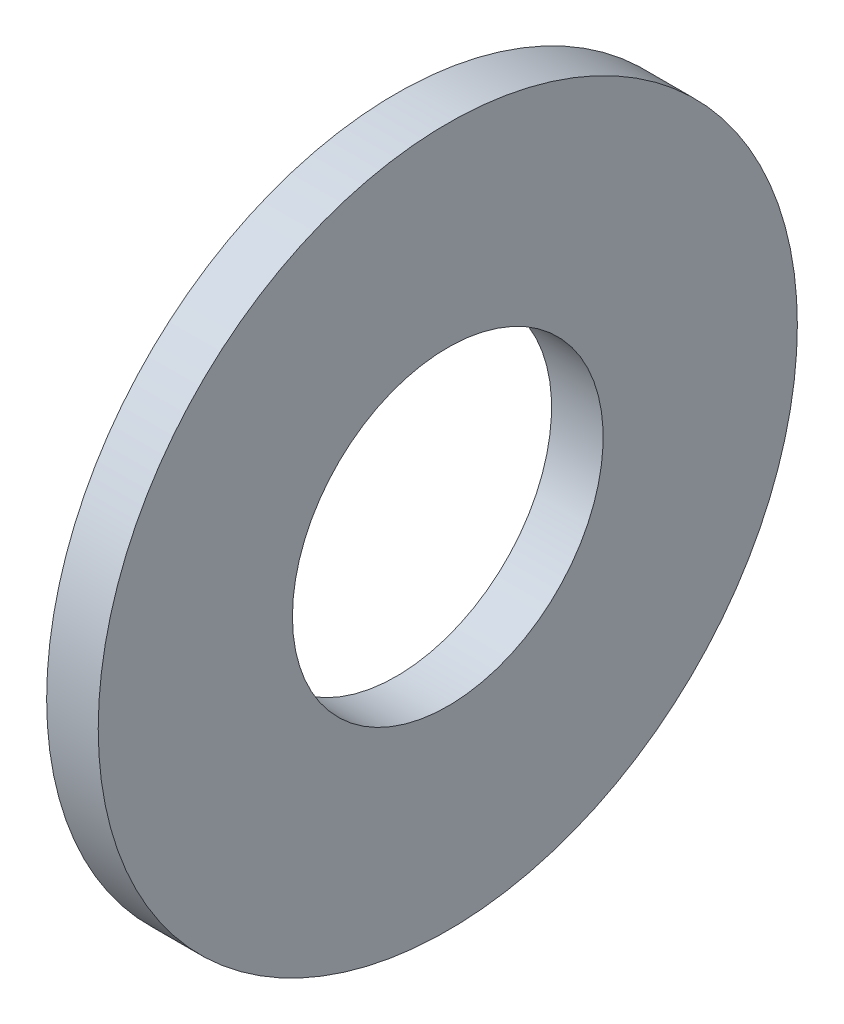
SolidWorks part; units mm, degrees
material "Plain Carbon Steel"
ref_plane "Plane1" through (0, 0, 0) normal (0, 0, 1) x (1, 0, 0)
ref_plane "Plane2" through (0, 0, 0) normal (0, 1, 0) x (1, 0, 0)
ref_plane "Plane3" through (0, 0, 0) normal (1, 0, 0) x (0, 0, -1)
sketch "Sketch1" plane through (0, 0, 0) normal (0, 0, 1) x (1, 0, 0)
  line L0 (-34.925, 0) -> (9.525, 0) construction
  line L1 (0, 6.35) -> (0, 14.2875)
  line L2 (0, 14.2875) -> (-2.1082, 14.2875)
  line L3 (-2.1082, 14.2875) -> (-2.1082, 6.35)
  line L4 (-2.1082, 6.35) -> (0, 6.35)
  dimension "Thickness" = 2.1082
  dimension "Inside_dia" = 12.7
  dimension "Outside_dia" = 28.575
revolve "Base-Revolve" add sketch "Sketch1" angle 360 about L0
